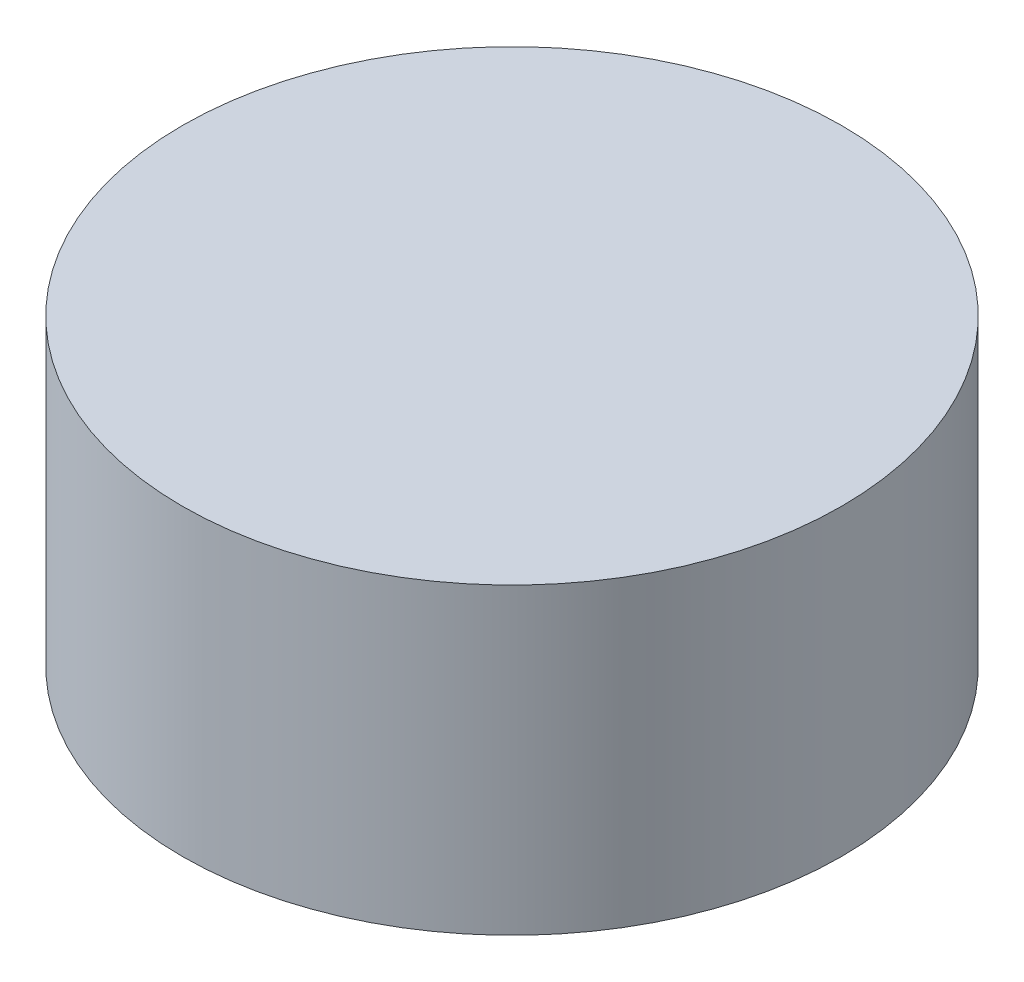
SolidWorks part; units mm, degrees
ref_plane "Front Plane" through (0, 0, 0) normal (0, 0, 1) x (1, 0, 0)
ref_plane "Top Plane" through (0, 0, 0) normal (0, 1, 0) x (1, 0, 0)
ref_plane "Right Plane" through (0, 0, 0) normal (1, 0, 0) x (0, 0, -1)
sketch "Sketch1" plane through (0, 0, 0) normal (0, 1, 0) x (1, 0, 0)
  circle A0 centre (0, 0) radius 50
sketch "Sketch2" plane through (0, 0, 0) normal (0, 0, 1) x (1, 0, 0)
  line L0 (0, 0) -> (0, -23) construction
  line L1 (0, 0) -> (0, 23) construction
  line L3 (-38.3022, -23) -> (-839.3423, -23) construction
extrude "Boss-Extrude1" add sketch "Sketch1" along normal up to vertex (23 mm away) and the other way up to vertex (23 mm away) contours A0 up to point (0, 23, 0) other way up to point (0, -23, 0)
ref_point "Point1"
sketch3d "3DSketch1"
  line L0 (0, 0, 0) -> (227.1966, 0, 0) construction
  line L1 (0, 0, 0) -> (0, 0, -241.2858)
  line L2 (0, -98, 0) -> (0, 214.4781, 0) construction
